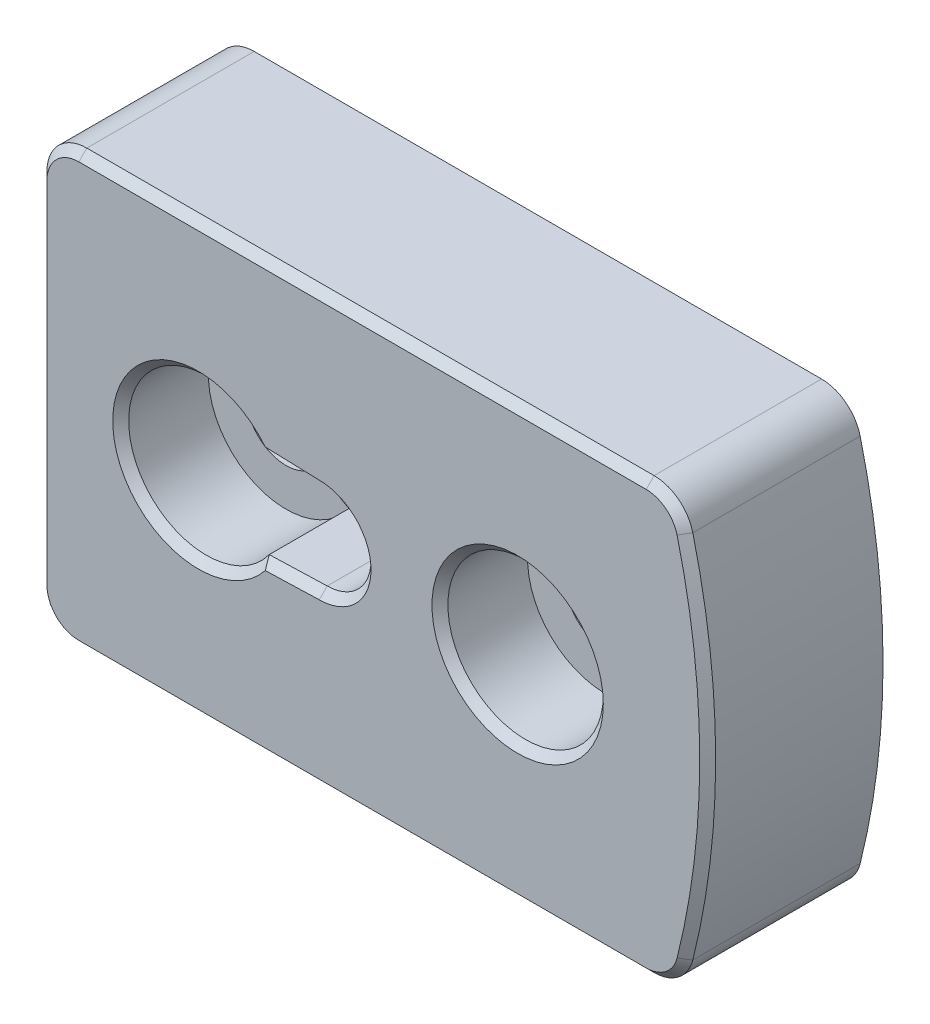
SolidWorks part; units mm, degrees
ref_plane "Front Plane" through (0, 0, 0) normal (0, 0, 1) x (1, 0, 0)
ref_plane "Top Plane" through (0, 0, 0) normal (0, 1, 0) x (1, 0, 0)
ref_plane "Right Plane" through (0, 0, 0) normal (1, 0, 0) x (0, 0, -1)
sketch "Sketch1" plane through (0, 0, 0) normal (0, 0, 1) x (1, 0, 0)
  line L0 (-10, 13.5) -> (-10, -13.5) construction
  line L1 (-20, -13.5) -> (20, -13.5)
  line L2 (-20, -13.5) -> (-20, 13.5)
  line L3 (-20, 13.5) -> (20, 13.5)
  line L5 (-20, -13.5) -> (20, 13.5) construction
  line L6 (-20, 13.5) -> (20, -13.5) construction
  line L7 (10.0266, 13.5) -> (10.0266, -13.5) construction
  line L8 (-8.92, 0) -> (-8.92, -38.6748) construction
  line L13 (-8.92, -38.6748) -> (-10.28, -38.6748) construction
  line L14 (-10.28, -38.6748) -> (-10.28, 0) construction
  line L15 (-2.42, 6.5) -> (43.4398, 6.5) construction
  line L16 (43.4398, 6.5) -> (43.4398, 7.86) construction
  line L17 (43.4398, 7.86) -> (-2.42, 7.86) construction
  line L18 (20, -13.5) -> (19.9199, -28.5934)
  circle A0 centre (-2.42, 0) radius 6.5
  arc A1 (-10.28, 0) -> (-2.42, 7.86) centre (-2.42, 0) cw construction
  arc A2 (20, 13.5) -> (20, -13.5) centre (-25.7558, 0) cw
  point P0 (-2.4466, -2.4466)
  point P7 (21.95, 0)
  dimension "D3" = 13
  dimension "D6" = 1.36
  dimension "D8" = 17.58
  dimension "D9" = 1.95
  dimension "D1" = 5.64
  dimension "D2" = 40
  dimension "D4" = 10
  dimension "D5" = 27
  dimension "D7" = 1.36
extrude "Boss-Extrude1" add sketch "Sketch1" along normal blind 11
sketch "Sketch2" plane through (0, 0, 11) normal (0, 0, 1) x (1, 0, 0)
  line L0 (-10, 13.5) -> (-10, -13.5) construction
  line L1 (10.0266, 13.5) -> (10.0266, -13.5) construction
  circle A0 centre (-10, 0) radius 2.5
  circle A1 centre (10.0266, 0) radius 2.5
  dimension "D1" = 5
extrude "Cut-Extrude1" cut sketch "Sketch2" against normal through all
sketch "Sketch3" plane through (0, 0, 11) normal (0, 0, 1) x (1, 0, 0)
  line L0 (-10, 13.5) -> (-10, -13.5) construction
  line L1 (10.0266, 13.5) -> (10.0266, -13.5) construction
  circle A0 centre (-10, 0) radius 4.875
  circle A1 centre (10.0266, 0) radius 4.875
  dimension "D1" = 9.75
extrude "Cut-Extrude2" cut sketch "Sketch3" against normal offset from surface (5.5 mm away) 5.5 up to face at (-7.5, 0, 0)
sketch "Sketch4" plane through (0, 0, 11) normal (0, 0, 1) x (1, 0, 0)
  circle A0 centre (-2.42, 0) radius 2.75
  dimension "D1" = 5.5
extrude "Cut-Extrude3" cut sketch "Sketch4" against normal through all
sketch "Sketch5" plane through (0, 0, 0) normal (0, 0, -1) x (-1, 0, 0)
  line L1 (6.72, -2.4826) -> (6.72, 2.4826)
  line L2 (6.72, 2.4826) -> (2.42, 4.9652)
  line L3 (2.42, 4.9652) -> (-1.88, 2.4826)
  line L4 (-1.88, 2.4826) -> (-1.88, -2.4826)
  line L5 (-1.88, -2.4826) -> (2.42, -4.9652)
  line L6 (2.42, -4.9652) -> (6.72, -2.4826)
  line L7 (20, -13.5) -> (20, 13.5) construction
  circle A0 centre (2.42, 0) radius 4.3 construction
  dimension "D1" = 8.6
extrude "Cut-Extrude4" cut sketch "Sketch5" against normal up to surface (5.5 mm away) up to face at (-10.0225, 0, 5.5)
fillet "Fillet1" radius 2.5 4 edges at (-20, -13.5, 5.5) (-20, 13.5, 5.5) (20, -13.5, 5.5) (20, 13.5, 5.5)
chamfer "Chamfer1" distance 0.5 angle 45 8 edges at (0.2956, -13.5, 11) (-19.2678, -12.7678, 11) (-20, 0, 11) (-19.2678, 12.7678, 11) (0.2956, 13.5, 11) (19.629, -12.9711, 11) (21.95, 0, 11) (19.629, 12.9711, 11)
sketch "Sketch6" plane through (0, 0, 11) normal (0, 0, 1) x (1, 0, 0)
  line L5 (-6.0563, 2.8658) -> (-2.42, 2.75)
  line L6 (-6.0563, -2.8658) -> (-2.42, -2.75)
  line L7 (-6.0563, 2.8658) -> (-2.42, 4.9652) construction
  line L9 (-6.0563, -2.8658) -> (-6.72, -2.4826)
  line L12 (-6.72, 2.4826) -> (-2.42, 4.9652) construction
  line L13 (-6.72, -2.4826) -> (-6.72, 2.4826)
  line L19 (-6.72, 2.4826) -> (-6.0563, 2.8658)
  arc A0 (-5.1412, -0.397) -> (-5.1412, 0.397) centre (-2.42, 0) ccw construction
  arc A1 (-6.0563, 2.8658) -> (-6.0563, -2.8658) centre (-10, 0) ccw construction
  arc A2 (-2.42, -2.75) -> (-2.42, 2.75) centre (-2.42, 0) ccw
  arc A4 (-5.1412, 0.397) -> (-5.1412, -0.397) centre (-10, 0) ccw construction
extrude "Cut-Extrude5" cut sketch "Sketch6" against normal through all and the other way through all
fillet "Fillet2" [suppressed] radius 3
chamfer "Chamfer3" distance 0.5 angle 45 5 edges at (14.9016, 0, 11) (-4.2381, -2.8079, 11) (0.33, 0, 11) (-4.2381, 2.8079, 11) (-14.875, 0, 11)
